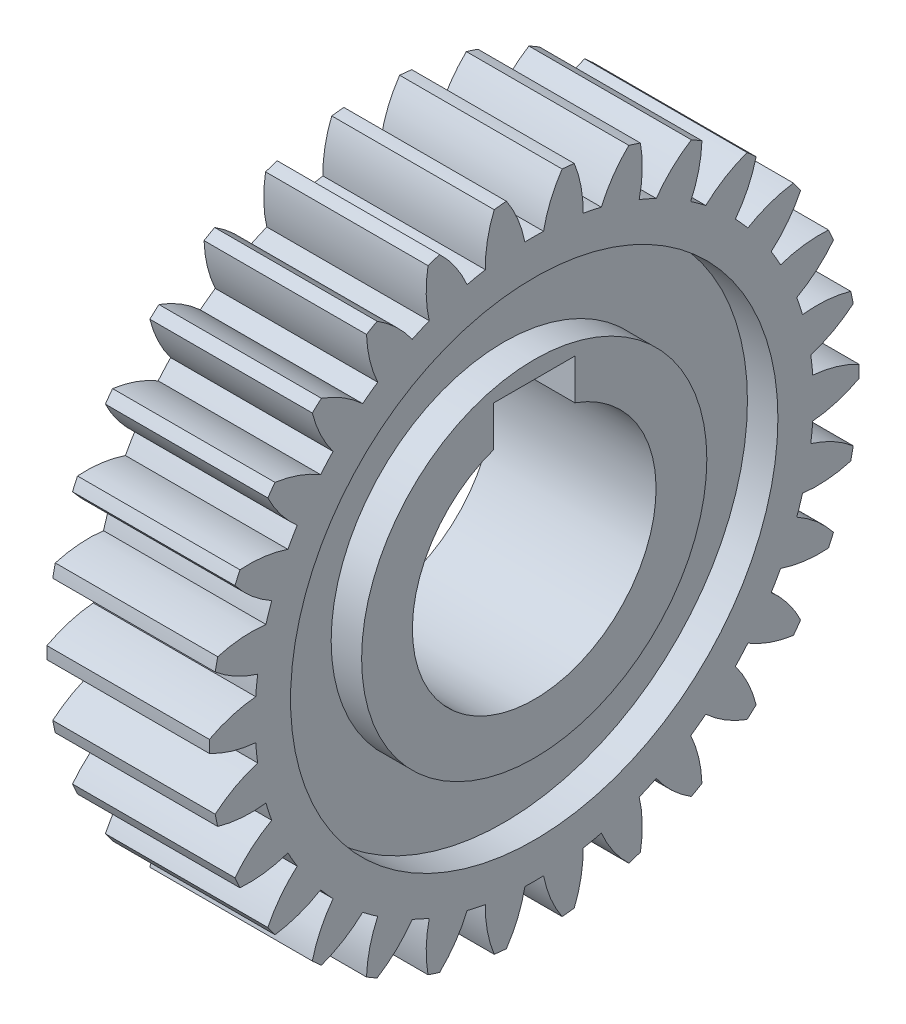
SolidWorks part; units mm, degrees
ref_plane "Plane1" through (0, 0, 0) normal (0, 0, 1) x (1, 0, 0)
ref_plane "Plane2" through (0, 0, 0) normal (0, 1, 0) x (1, 0, 0)
ref_plane "Plane3" through (0, 0, 0) normal (1, 0, 0) x (0, 0, -1)
sketch "HoldingSke" plane through (0, 0, 0) normal (0, 1, 0) x (1, 0, 0)
  line L0 (0, 0) -> (0.433, -0.25)
  line L1 (-15, 0) -> (100, 0) construction
  line L2 (0, 0) -> (-2.1039, 2.3779)
  line L3 (0, 0) -> (-11.863, 4.5341)
  line L4 (0, 0) -> (7.479, 4.318)
  line L5 (0, 0) -> (-46.8476, -17.4728)
  line L6 (0, 0) -> (-13.2634, -8.9489)
  line L7 (-2.1039, 2.3779) -> (8.6586, 51.2059)
  line L8 (-76.2, 54.61) -> (-72.9, 54.61)
  line L9 (-71.009, 38.7566) -> (-53.1078, 45.2721)
  line L10 (-76.2, 71.12) -> (104.1128, 71.12)
  line L11 (0, 0) -> (-16, 0)
  line L12 (-76.2, 101.6) -> (-76.133, 101.6)
  line L13 (24.9733, 27.94) -> (52.9518, 28.4284)
  line L14 (24.9733, 27.94) -> (24.9743, 27.94)
  line L15 (24.9733, 27.94) -> (100.4006, 29.5858)
  line L16 (-63.627, -2) -> (-12.827, -2)
  circle A0 centre (0, 0) radius 12
  circle A1 centre (0, 0) radius 27.499
  circle A2 centre (0, 0) radius 37.5
  circle A3 centre (0, 0) radius 12
  dimension "MHD" = 54.998
  dimension "Hub_dia" = 75
  dimension "Bore" = 24
  dimension "MBD" = 24
  dimension "Num_teeth" = 30
  dimension "Pitch" = 0.5
  dimension "Overall_len" = 50
  dimension "Show_teeth" = 30
  dimension "Thickness" = 16
  dimension "OAL" = 50.0001
  dimension "T_dim" = 3.3
  dimension "Ap" = 20
  dimension "H" = 19.05
  dimension "Pitch_radius" = 180.3128
  dimension "Width" = 16
  dimension "Backlash" = 0.067
  dimension "Addendum_fac" = 1
  dimension "Dedendum_fac" = 1.25
  dimension "Clearance_fac" = 0.25
  dimension "Dedendum_add" = 0.001
  dimension "Module" = 2
sketch "BasProSke" plane through (0, 0, 0) normal (0, 1, 0) x (1, 0, 0)
  line L0 (-10, 0) -> (60, 0) construction
  line L1 (0, 0) -> (0, 32)
  line L2 (0, 0) -> (16, 0)
  line L3 (16, 0) -> (16, 32)
  line L4 (16, 32) -> (0, 32)
  dimension "Thickness" = 16
  dimension "Diameter" = 64
revolve "Base-Revolve" add sketch "BasProSke" angle 360 about L0
sketch "TooCutSke" plane through (0, 0, 0) normal (1, 0, 0) x (0, 0, -1)
  line L1 (0, 0) -> (0, 107) construction
  line L2 (0, 0) -> (-1.6873, 29.9525) construction
  line L3 (0, 0) -> (-6.2643, 59.6013) construction
  line L4 (-1.6873, 29.9525) -> (-3.1322, 29.8007) construction
  arc A0 (0.9186, 27.4837) -> (-0.9186, 27.4837) centre (0, 0) ccw
  arc A1 (2.7618, 31.9061) -> (-2.7618, 31.9061) centre (0, 0) ccw
  circle A2 centre (0, 0) radius 30 construction
  circle A3 centre (0, 0) radius 28.1908 construction
  arc A4 (-0.9186, 27.4837) -> (-2.7618, 31.9061) centre (-12.6936, 25.1712) ccw
  arc A5 (2.7618, 31.9061) -> (0.9186, 27.4837) centre (12.6936, 25.1712) ccw
  dimension "Root_dia" = 54.998
  dimension "Overcut_dia" = 64.0508
  dimension "Pitch_dia" = 60
  dimension "Base_dia" = 56.3816
  dimension "Flank_rad" = 12
  dimension "Half_ang" = 6
  dimension "Half_CT" = 1.4528
extrude "ToothCut" cut sketch "TooCutSke" along normal through all
fillet "Breaks" [suppressed] radius 0.04
fillet "RootFillets" [suppressed] radius 0.501
pattern_circular "TeethCuts" count 30 every 12 about axis through (-10, 0, 0) along (1, 0, 0) of "ToothCut", "RootFillets", "Breaks"
sketch "HubNeaOneSke" plane through (0, 0, 0) normal (-1, 0, 0) x (0, 0, 1)
  circle A0 centre (0, 0) radius 27.499
  dimension "Diameter" = 54.998
extrude "HubNearOne" [suppressed] add sketch "HubNeaOneSke" along normal blind 34.0001
sketch "HubNeaBotSke" plane through (0, 0, 0) normal (-1, 0, 0) x (0, 0, 1)
  circle A0 centre (0, 0) radius 27.499
  dimension "Diameter" = 54.998
extrude "HubNearBoth" [suppressed] add sketch "HubNeaBotSke" along normal blind 17
ref_plane "FarPln" through (16, 0, 0) normal (1, 0, 0) x (0, 0, -1)
sketch "HubFarSke" plane through (16, 0, 0) normal (1, 0, 0) x (0, 0, -1)
  circle A0 centre (0, 0) radius 27.499
  dimension "Diameter" = 54.998
extrude "HubFar" [suppressed] add sketch "HubFarSke" along normal blind 17
sketch "BorSke" plane through (0, 0, 0) normal (1, 0, 0) x (0, 0, -1)
  circle A0 centre (0, 0) radius 12
  dimension "Diameter" = 24
extrude "Bore" cut sketch "BorSke" along normal mid plane 100.0001
sketch "KeySke" plane through (0, 0, 0) normal (1, 0, 0) x (0, 0, -1)
  line L0 (-4, 0) -> (-4, 15.3)
  line L1 (-4, 15.3) -> (4, 15.3)
  line L2 (4, 15.3) -> (4, 0)
  line L3 (0, 0) -> (0, 34) construction
  line L4 (-4, 0) -> (4, 0)
  dimension "Offset" = 15.3
  dimension "Width" = 8
extrude "Keyway" [suppressed] cut sketch "KeySke" along normal mid plane 100.0001
pattern_circular "Keyway2" [suppressed] count 2 every 90 about axis through (-10, 0, 0) along (1, 0, 0)
sketch "Schizzo1" plane through (16, 0, 0) normal (1, 0, 0) x (0, 0, -1)
  circle A0 centre (0, 0) radius 17
  circle A1 centre (0, 0) radius 24
  dimension "D1" = 34
  dimension "D2" = 48
extrude "Taglio-Estrusione1" cut sketch "Schizzo1" against normal blind 3
ref_plane "Piano1" through (8, 0, 0) normal (1, 0, 0) x (0, 0, -1)
mirror "Specchia1" about plane through (8, 0, 0) normal (1, 0, 0) of "Taglio-Estrusione1"
sketch "Schizzo2" plane through (16, 0, 0) normal (1, 0, 0) x (0, 0, -1)
  line L0 (-4, 15.3) -> (4, 15.3)
  line L1 (-7.2824, 0) -> (0, 0) construction
  line L2 (-4, 15.3) -> (-4, 11.3137)
  line L3 (4, 15.3) -> (4, 11.3137)
  circle A0 centre (0, 0) radius 12 construction
  arc A1 (-4, 11.3137) -> (4, 11.3137) centre (0, 0) cw
  circle M3 centre (0, 0) radius 12
  dimension "D1" = 15.3
  dimension "D2" = 8
  dimension "D3" = 4
extrude "Taglio-Estrusione2" cut sketch "Schizzo2" against normal through all contours L3 L0 L2 M3
equation "' \"Module@HoldingSke\" = 6.35"
equation "' \"Num_teeth@HoldingSke\" = 12"
equation "' \"Ap@HoldingSke\" =  20"
equation "' \"Ap@HoldingSke\" = 20"
equation "' \"Width@HoldingSke\" = 0.5 * 25.4"
equation "' \"Hub_dia@HoldingSke\"= 1 * 25.4"
equation "' \"Hub_dia@HoldingSke\" = 1 * 25.4"
equation "' \"Overall_len@HoldingSke\" = 1.0 * 25.4"
equation "' \"Bore@HoldingSke\" = 0.75 * 25.4"
equation "' \"T_dim@HoldingSke\" = 0.1 * 25.4"
equation "' \"Width@KeySke\" = 0.25 * 25.4"
equation "' \"Show_teeth@HoldingSke\" = 13"
equation "' \"Backlash@HoldingSke\" = 0.009 * 25.4"
equation "' \"Addendum_fac@HoldingSke\" = 1.0"
equation "' \"Dedendum_fac@HoldingSke\" = 1.25"
equation "' \"Dedendum_add@HoldingSke\" = 0.00005 * 25.4"
equation "' \"Clearance_fac@HoldingSke\" = 0.25"
equation "\"Pitch@HoldingSke\" = 1 / \"Module@HoldingSke\""
equation "\"Overcut_dia@TooCutSke\" = (\"Num_teeth@HoldingSke\" + 2 * \"Addendum_fac@HoldingSke\") / \"Pitch@HoldingSke\" + 0.002 * 25.4"
equation "\"Pitch_dia@TooCutSke\" = \"Num_teeth@HoldingSke\" / \"Pitch@HoldingSke\""
equation "\"Base_dia@TooCutSke\" = \"Num_teeth@HoldingSke\" / \"Pitch@HoldingSke\" * cos((\"Ap@HoldingSke\"  * 3.14159265 / 180))"
equation "\"Root_dia@TooCutSke\" = (\"Num_teeth@HoldingSke\" + 2) / \"Pitch@HoldingSke\" - 2 * (\"Addendum_fac@HoldingSke\" + \"Dedendum_fac@HoldingSke\") / \"Pitch@HoldingSke\" - \"Dedendum_add@HoldingSke\" * 2"
equation "\"Half_ang@TooCutSke\" = 180 / \"Num_teeth@HoldingSke\""
equation "\"Half_CT@TooCutSke\" = \"Num_teeth@HoldingSke\" / \"Pitch@HoldingSke\" * sin((3.14159265 / 2 / \"Num_teeth@HoldingSke\")) / 2 - 7 * \"Backlash@HoldingSke\" / 4"
equation "\"Flank_rad@TooCutSke\" = \"Num_teeth@HoldingSke\" / \"Pitch@HoldingSke\" / 5"
equation "\"Radius@RootFillets\" = \"Clearance_fac@HoldingSke\" / \"Pitch@HoldingSke\" + \"Dedendum_add@HoldingSke\""
equation "\"Break_rad@Breaks\" = 0.02 / \"Pitch@HoldingSke\""
equation "\"Thickness@HoldingSke\" = \"Width@HoldingSke\""
equation "\"OAL@HoldingSke\" = \"Thickness@HoldingSke\""
equation "\"MHD@HoldingSke\" = (\"Num_teeth@HoldingSke\" + 2) / \"Pitch@HoldingSke\" - 2 * (\"Addendum_fac@HoldingSke\" + \"Dedendum_fac@HoldingSke\")  / \"Pitch@HoldingSke\" - \"Dedendum_add@HoldingSke\" * 2"
equation "\"MBD@HoldingSke\" = (\"Num_teeth@HoldingSke\" + 2) / \"Pitch@HoldingSke\" - 2 * (\"Addendum_fac@HoldingSke\" + \"Dedendum_fac@HoldingSke\")  / \"Pitch@HoldingSke\" - \"Dedendum_add@HoldingSke\" * 2 - 0.002 * 25.4"
equation "\"MHD@HoldingSke\" = ((sgn( \"MHD@HoldingSke\" - \"Hub_dia@HoldingSke\" )-1)*( \"MHD@HoldingSke\" - \"Hub_dia@HoldingSke\" ))/-2+ \"Hub_dia@HoldingSke\""
equation "\"MBD@HoldingSke\" = ((sgn( \"MBD@HoldingSke\" - \"Bore@HoldingSke\" )-1)*( \"MBD@HoldingSke\" - \"Bore@HoldingSke\" ))/-2+ \"Bore@HoldingSke\""
equation "\"OAL@HoldingSke\" = ((sgn( \"OAL@HoldingSke\" - \"Overall_len@HoldingSke\" )+1)*( \"OAL@HoldingSke\" - \"Overall_len@HoldingSke\" ))/2 + \"Overall_len@HoldingSke\" + 0.000002 * 25.4"
equation "\"Num_teeth@TeethCuts\" = int( \"Show_teeth@HoldingSke\" ) + 1"
equation "\"Num_teeth@TeethCuts\" = ((sgn( \"Num_teeth@TeethCuts\" - \"Num_teeth@HoldingSke\" )-1)*( \"Num_teeth@TeethCuts\" - \"Num_teeth@HoldingSke\" ))/-2+ \"Num_teeth@HoldingSke\""
equation "\"Num_teeth@TeethCuts\" = ((sgn( \"Num_teeth@TeethCuts\" - 2.0)+1)*( \"Num_teeth@TeethCuts\" - 2.0))/2 +2.0"
equation "\"Angle@TeethCuts\" = 360.0 / \"Num_teeth@HoldingSke\""
equation "\"Diameter@BasProSke\" = (\"Num_teeth@HoldingSke\" + 2 * \"Addendum_fac@HoldingSke\") / \"Pitch@HoldingSke\""
equation "\"Thickness@BasProSke\"  = \"Thickness@HoldingSke\""
equation "' \"Fillet_rad@BasProSke\" =  \"Thickness@HoldingSke\" * 0.05"
equation "' \"Fillet_rad@BasProSke\" = \"Thickness@HoldingSke\" * 0.05"
equation "\"MHD@HoldingSke\" = ((sgn( \"MHD@HoldingSke\" - \"Root_dia@TooCutSke\" )-1)*( \"MHD@HoldingSke\" - \"Root_dia@TooCutSke\" ))/-2+ \"Root_dia@TooCutSke\""
equation "\"Diameter@HubNeaOneSke\" = \"MHD@HoldingSke\""
equation "\"Length@HubNearOne\" = \"OAL@HoldingSke\" - \"Thickness@BasProSke\""
equation "\"Diameter@HubNeaBotSke\" = \"MHD@HoldingSke\""
equation "\"Length@HubNearBoth\" = ( \"OAL@HoldingSke\" - \"Thickness@BasProSke\" ) / 2.0"
equation "\"Thickness@FarPln\" = \"Thickness@BasProSke\""
equation "\"Diameter@HubFarSke\" = \"MHD@HoldingSke\""
equation "\"Length@HubFar\" = ( \"OAL@HoldingSke\" - \"Thickness@BasProSke\" ) / 2.0"
equation "\"Diameter@BorSke\" = \"MBD@HoldingSke\""
equation "\"D1@Bore\" = \"OAL@HoldingSke\" * 2.0"
equation "\"D1@Keyway\" = \"OAL@HoldingSke\" * 2.0"
equation "\"Offset@KeySke\" = \"T_dim@HoldingSke\" + \"MBD@HoldingSke\" / 2.0"
